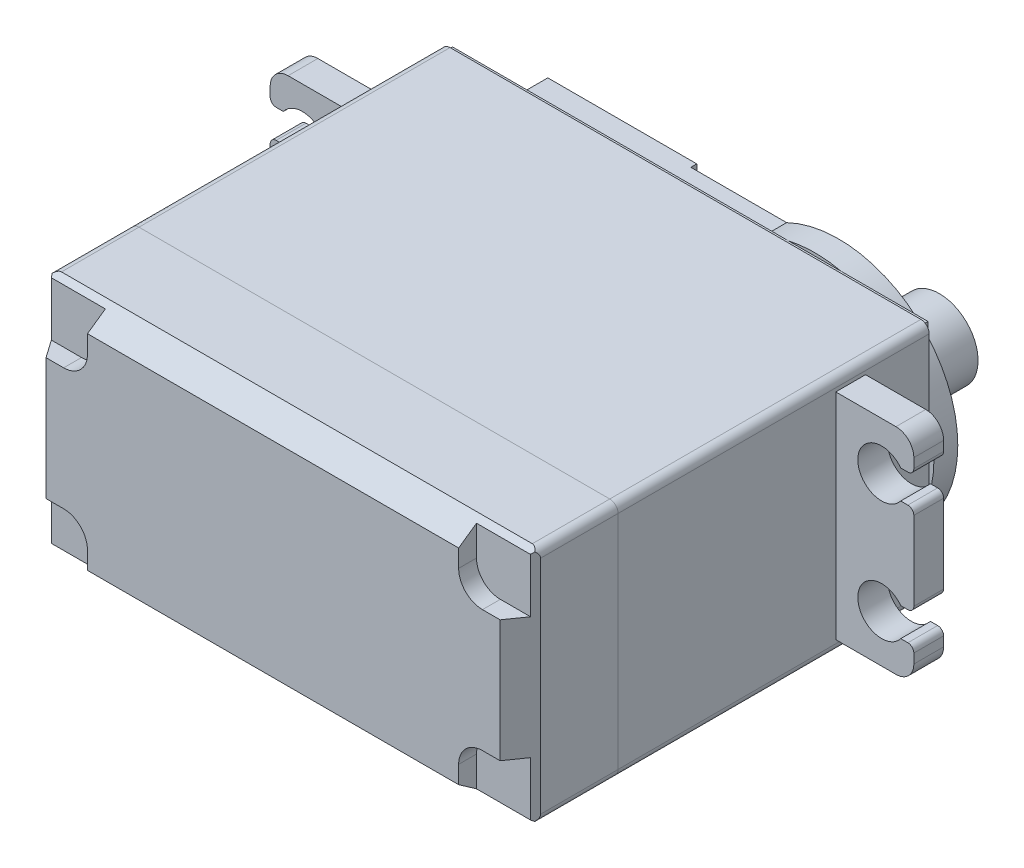
SolidWorks part; units mm, degrees
ref_plane "Front Plane" through (0, 0, 0) normal (0, 0, 1) x (1, 0, 0)
ref_plane "Top Plane" through (0, 0, 0) normal (0, 1, 0) x (1, 0, 0)
ref_plane "Right Plane" through (0, 0, 0) normal (1, 0, 0) x (0, 0, -1)
sketch "Sketch1" plane through (0, 0, 0) normal (0, 0, 1) x (1, 0, 0)
  line L1 (20.45, 10) -> (-20.45, 10)
  line L2 (20.45, 10) -> (20.45, -10)
  line L3 (20.45, -10) -> (-20.45, -10)
  line L4 (-20.45, 10) -> (-20.45, -10)
  line L5 (20.45, 10) -> (-20.45, -10) construction
  line L6 (20.45, -10) -> (-20.45, 10) construction
  point P0 (0, 0)
  dimension "D1" = 20
  dimension "D2" = 40.9
extrude "Boss-Extrude1" add sketch "Sketch1" along normal blind 19.3
sketch "Sketch2" plane through (0, 0, 0) normal (0, 0, -1) x (-1, 0, 0)
  line L4 (20.45, -10) -> (20.45, 10)
  line L5 (20.45, 10) -> (-20.45, 10)
  line L6 (-20.45, 10) -> (-20.45, -10)
  line L7 (-20.45, -10) -> (20.45, -10)
  line L8 (20.45, -10) -> (20.45, 10)
  line L9 (20.45, 10) -> (-20.45, 10)
  line L10 (-20.45, 10) -> (-20.45, -10)
  line L11 (-20.45, -10) -> (20.45, -10)
  dimension "D1" = 0
extrude "Boss-Extrude2" add sketch "Sketch2" along normal blind 6.8 separate body
sketch "Sketch3" plane through (0, 0, 19.3) normal (0, 0, 1) x (1, 0, 0)
  line L4 (-20.45, 10) -> (-20.45, -10)
  line L5 (-20.45, -10) -> (20.45, -10)
  line L6 (20.45, -10) -> (20.45, 10)
  line L7 (20.45, 10) -> (-20.45, 10)
  line L8 (-20.45, 10) -> (-20.45, -10)
  line L9 (-20.45, -10) -> (20.45, -10)
  line L10 (20.45, -10) -> (20.45, 10)
  line L11 (20.45, 10) -> (-20.45, 10)
  dimension "D1" = 0
extrude "Boss-Extrude3" add sketch "Sketch3" along normal blind 8.5 separate body
chamfer "Chamfer1" distance 2 angle 35 4 edges at (20.45, 0, 27.8) (0, -10, 27.8) (-20.45, 0, 27.8) (0, 10, 27.8)
sketch "Sketch4" plane through (0, 0, 27.8) normal (0, 0, 1) x (1, 0, 0)
  line L0 (0, 0) -> (0, 10) construction
  line L1 (-20.45, 10) -> (-15.57, 10)
  line L2 (-20.45, 10) -> (-20.45, 5.12)
  line L3 (-20.45, 5.12) -> (-17.57, 5.12)
  line L4 (-15.57, 10) -> (-15.57, 7.12)
  line L5 (-20.45, 10) -> (20.45, 10) construction
  line L6 (0, 0) -> (20.45, 0) construction
  line L7 (20.45, 10) -> (20.45, -10) construction
  line L8 (15.57, 10) -> (15.57, 7.12)
  line L9 (20.45, 5.12) -> (17.57, 5.12)
  line L10 (20.45, 10) -> (20.45, 5.12)
  line L11 (20.45, 10) -> (15.57, 10)
  line L12 (-15.57, -10) -> (-15.57, -7.12)
  line L13 (-20.45, -5.12) -> (-17.57, -5.12)
  line L14 (-20.45, -10) -> (-20.45, -5.12)
  line L15 (-20.45, -10) -> (-15.57, -10)
  line L16 (20.45, -10) -> (15.57, -10)
  line L17 (20.45, -10) -> (20.45, -5.12)
  line L18 (20.45, -5.12) -> (17.57, -5.12)
  line L19 (15.57, -10) -> (15.57, -7.12)
  arc A0 (-17.57, 5.12) -> (-15.57, 7.12) centre (-17.57, 7.12) ccw
  arc A1 (17.57, 5.12) -> (15.57, 7.12) centre (17.57, 7.12) cw
  arc A2 (-17.57, -5.12) -> (-15.57, -7.12) centre (-17.57, -7.12) cw
  arc A3 (17.57, -5.12) -> (15.57, -7.12) centre (17.57, -7.12) ccw
  dimension "D3" = 2
  dimension "D1" = 4.88
  dimension "D2" = 4.88
extrude "Cut-Extrude1" cut sketch "Sketch4" against normal blind 1.5
sketch "Sketch5" plane through (0, 0, -6.8) normal (0, 0, -1) x (-1, 0, 0)
  line L1 (19.95, 9.75) -> (-19.95, 9.75)
  line L2 (19.95, 9.75) -> (19.95, -9.75)
  line L3 (19.95, -9.75) -> (-19.95, -9.75)
  line L4 (-19.95, 9.75) -> (-19.95, -9.75)
  line L5 (19.95, 9.75) -> (-19.95, -9.75) construction
  line L6 (19.95, -9.75) -> (-19.95, 9.75) construction
  line L7 (20.45, 10) -> (-20.45, 10) construction
  line L8 (20.45, -10) -> (20.45, 10) construction
  point P0 (0, 0)
  dimension "D1" = 0.25
  dimension "D2" = 0.5
extrude "Boss-Extrude4" add sketch "Sketch5" along normal blind 0.4
sketch "Sketch7" plane through (0, 0, -7.2) normal (0, 0, -1) x (-1, 0, 0)
  line L0 (-20.45, 0) -> (20.45, 0) construction
  line L1 (-20.45, 10) -> (-20.45, -10) construction
  line L2 (20.45, -10) -> (20.45, 10) construction
  line L3 (20.45, 10) -> (-20.45, 10) construction
  line L4 (-6.09, 9.75) -> (-6.09, -9.75) construction
  line L5 (19.95, 9.75) -> (-19.95, 9.75) construction
  line L6 (-19.95, -9.75) -> (19.95, -9.75) construction
  line L7 (-6.09, 8.9995) -> (14.45, 8.9995)
  line L8 (14.45, 8.9995) -> (14.45, 3.9188)
  line L9 (14.45, -8.9995) -> (14.45, -3.9188)
  line L10 (-6.09, -8.9995) -> (14.45, -8.9995)
  arc A0 (-6.09, 8.9995) -> (-6.09, -8.9995) centre (-10.45, 0) ccw
  arc A1 (14.45, -3.9188) -> (14.45, 3.9188) centre (13.3905, 0) ccw
  point P23 (17.45, 0)
  dimension "D1" = 14.36
  dimension "D2" = 6
  dimension "D3" = 3
extrude "Boss-Extrude5" add sketch "Sketch7" along normal blind 2
sketch "Sketch8" plane through (0, 0, -9.2) normal (0, 0, -1) x (-1, 0, 0)
  circle A0 centre (-11.9002, 0) radius 6.5
  dimension "D1" = 13
extrude "Boss-Extrude6" add sketch "Sketch8" along normal blind 1.5
sketch "Sketch9" plane through (0, 0, -10.7) normal (0, 0, -1) x (-1, 0, 0)
  circle A0 centre (-11.9002, 0) radius 5.5
  dimension "D1" = 11
extrude "Boss-Extrude7" add sketch "Sketch9" along normal blind 0.5
sketch "Sketch10" plane through (0, 0, -11.2) normal (0, 0, -1) x (-1, 0, 0)
  circle A0 centre (-11.9002, 0) radius 3.25
  dimension "D1" = 6.5
extrude "Boss-Extrude8" add sketch "Sketch10" along normal blind 5
sketch "Sketch11" plane through (0, 0, -9.2) normal (0, 0, -1) x (-1, 0, 0)
  line L0 (-6.09, -8.9995) -> (14.45, -8.9995) construction
  line L1 (14.45, 8.9995) -> (1.95, 8.9995)
  line L2 (14.45, 8.9995) -> (14.45, -8.9995)
  line L3 (14.45, -8.9995) -> (1.95, -8.9995)
  line L4 (1.95, 8.9995) -> (1.95, 1.75)
  line L5 (13.45, 7.9995) -> (2.95, 7.9995)
  line L6 (2.95, 7.9995) -> (2.95, -7.9995)
  line L7 (13.45, -7.9995) -> (2.95, -7.9995)
  line L8 (13.45, 7.9995) -> (13.45, -7.9995)
  line L9 (1.95, -1.75) -> (1.95, -8.9995)
  line L10 (1.95, 8.9995) -> (1.95, -8.9995) construction
  arc A0 (1.95, 1.75) -> (1.95, -1.75) centre (1.95, 0) ccw
  dimension "D3" = 3.5
  dimension "D1" = 12.5
  dimension "D2" = 1
extrude "Boss-Extrude9" add sketch "Sketch11" along normal blind 0.5
fillet "Fillet1" radius 0.7 4 edges at (-20.45, -10, 9.65) (-20.45, 10, 9.65) (20.45, 10, 9.65) (20.45, -10, 9.65)
fillet "Fillet2" radius 0.7 4 edges at (20.45, 10, -3.4) (-20.45, 10, -3.4) (-20.45, -10, -3.4) (20.45, -10, -3.4)
fillet "Fillet3" radius 0.7 4 edges at (-20.45, 10, 22.55) (-20.45, -10, 22.55) (20.45, 10, 22.55) (20.45, -10, 22.55)
sketch "Sketch12" plane through (0, 0, -7.2) normal (0, 0, -1) x (-1, 0, 0)
  line L0 (20.45, 9) -> (25.5, 9)
  line L1 (20.45, -9.3) -> (20.45, 9.3) construction
  line L2 (0, 0) -> (30.9499, 0) construction
  line L3 (27, 7.5) -> (27, 6.7)
  line L4 (19.75, 10) -> (-19.75, 10) construction
  line L5 (0, 8.9995) -> (0, -8.9995) construction
  line L6 (1.95, 8.9995) -> (-6.09, 8.9995) construction
  line L7 (-6.09, -8.9995) -> (1.95, -8.9995) construction
  line L8 (25.9, 9) -> (25.9, 0) construction
  line L9 (25.9, 6.2) -> (26.5, 6.2)
  line L10 (25.9, 3.8) -> (26.5, 3.8)
  line L11 (27, 3.3) -> (27, -3.3)
  line L12 (25.9, -3.8) -> (26.5, -3.8)
  line L13 (25.9, -6.2) -> (26.5, -6.2)
  line L14 (27, -7.5) -> (27, -6.7)
  line L15 (20.45, -9) -> (25.5, -9)
  line L16 (20.45, 9) -> (20.45, -9)
  arc A0 (25.9, 6.2) -> (25.9, 3.8) centre (24.3, 5) ccw
  arc A1 (26.5, 3.8) -> (27, 3.3) centre (26.5, 3.3) cw
  arc A2 (26.5, 6.2) -> (27, 6.7) centre (26.5, 6.7) ccw
  arc A3 (25.5, 9) -> (27, 7.5) centre (25.5, 7.5) cw
  arc A4 (25.5, -9) -> (27, -7.5) centre (25.5, -7.5) ccw
  arc A5 (26.5, -6.2) -> (27, -6.7) centre (26.5, -6.7) cw
  arc A6 (26.5, -3.8) -> (27, -3.3) centre (26.5, -3.3) ccw
  arc A7 (25.9, -6.2) -> (25.9, -3.8) centre (24.3, -5) cw
  point P25 (27, 3.8)
  point P42 (27, 0)
  point P43 (27, -3.8)
  dimension "D3" = 4
  dimension "D7" = 0.5
  dimension "D8" = 1.5
  dimension "D1" = 6.55
  dimension "D2" = 1
  dimension "D4" = 5
  dimension "D5" = 24.3
  dimension "D6" = 1.1
extrude "Boss-Extrude10" add sketch "Sketch12" against normal blind 2.5 from offset 5.74 offset against normal yes
mirror "Mirror1" about plane through (0, 0, 0) normal (1, 0, 0) of "Boss-Extrude10"
